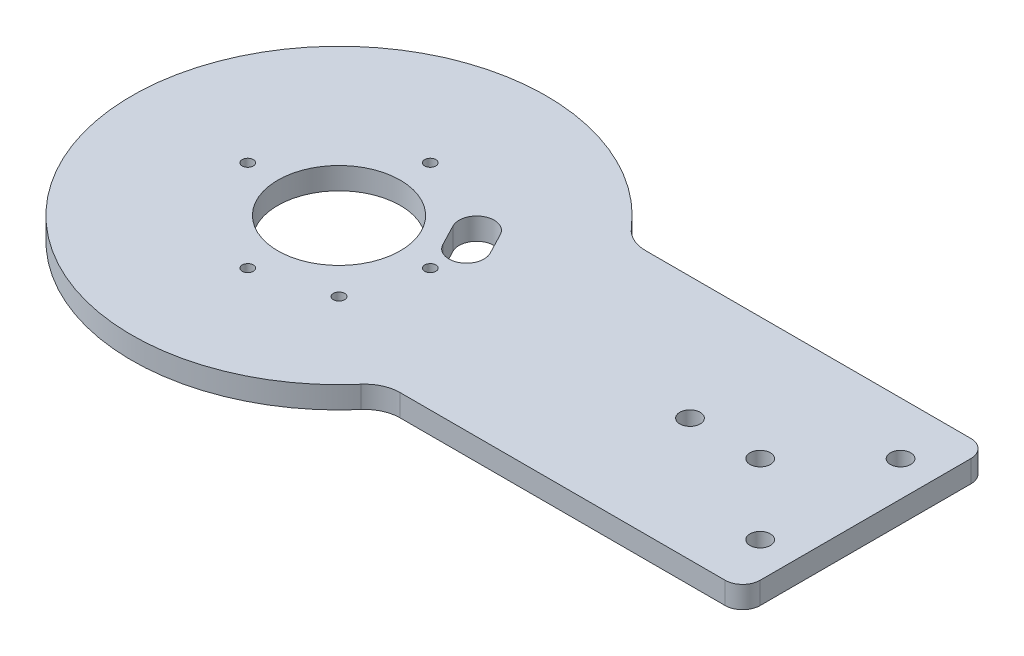
SolidWorks part; units mm, degrees
material "Acrylic (Medium-high impact)"
ref_plane "Front" through (0, 0, 0) normal (0, 0, 1) x (1, 0, 0)
ref_plane "Top" through (0, 0, 0) normal (0, 1, 0) x (1, 0, 0)
ref_plane "Right" through (0, 0, 0) normal (1, 0, 0) x (0, 0, -1)
sketch "Sketch1" plane through (0, 0, 0) normal (0, 1, 0) x (1, 0, 0)
  line L0 (177.8, 0) -> (0, 0) construction
  line L1 (190.5, -44.45) -> (60.41, -44.45)
  line L2 (190.5, 44.45) -> (60.41, 44.45)
  line L3 (190.5, 44.45) -> (190.5, -44.45)
  circle A2 centre (0, 0) radius 21.9583 construction
  arc A4 (60.41, 44.45) -> (60.41, -44.45) centre (0, 0) ccw
  point P3 (0, 0)
  dimension "D1" = 177.8
  dimension "D3" = 43.9166
  dimension "D4" = 44.45
  dimension "D5" = 75.0011
  dimension "D2" = 88.9
  dimension "D6" = 12.7
extrude "Boss-Extrude1" add sketch "Sketch1" along normal blind 7.9375
sketch "Sketch23" plane through (0, 0, 0) normal (0, -1, 0) x (1, 0, 0)
  line L0 (29.5483, -20.2499) -> (33.5359, -12.5897) construction
  line L1 (23.9158, -17.3178) -> (27.9034, -9.6576)
  line L2 (35.1808, -23.182) -> (39.1685, -15.5218)
  line L3 (0, 0) -> (-86.9571, 0) construction
  line L4 (29.5483, -20.2499) -> (0, 0) construction
  line L5 (0, 0) -> (33.5359, -12.5897) construction
  line L6 (0, 0) -> (31.5421, -16.4198) construction
  circle A0 centre (0, 0) radius 22.1615
  circle A1 centre (0, 0) radius 33.02 construction
  circle A2 centre (0, 33.02) radius 2.0193
  circle A3 centre (33.02, 0) radius 2.0193
  circle A4 centre (0, -33.02) radius 2.0193
  circle A5 centre (-33.02, 0) radius 2.0193
  circle A6 centre (25.4, 25.4) radius 2.0193
  arc A7 (23.9158, -17.3178) -> (35.1808, -23.182) centre (29.5483, -20.2499) ccw
  arc A8 (39.1685, -15.5218) -> (27.9034, -9.6576) centre (33.5359, -12.5897) ccw
  point P16 (31.5421, -16.4198)
  dimension "D1" = 44.323
  dimension "D3" = 4.0386
  dimension "D7" = 6.35
  dimension "D2" = 33.02
  dimension "D4" = 25.4
  dimension "D5" = 25.4
  dimension "D6" = 27.5
  dimension "D8" = 8.636
  dimension "D9" = 35.56
extrude "Cut-Extrude4" cut sketch "Sketch23" against normal through all
hole_wizard "L (0.29) Diameter Hole1" positions "Sketch21" profile "Sketch22" hole size "L" standard "ANSI Inch" end condition through all
sketch "Sketch21" plane through (0, 7.9375, 0) normal (0, 1, 0) x (1, 0, 0)
  line L0 (177.8, -25.4) -> (177.8, 25.4) construction
  line L3 (190.5, -44.45) -> (190.5, 44.45) construction
  point P0 (177.8, 25.4)
  point P2 (177.8, -25.4)
  point P11 (177.8, 0)
  point P20 (152.4, 0)
  point P27 (127, 0)
  dimension "D1" = 50.8
  dimension "D2" = 12.7
  dimension "D3" = 25.4
  dimension "D4" = 25.4
sketch "Sketch22" plane through (177.8, 7.9375, -25.4) normal (1, 0, 0) x (0, 0, 1)
  line L0 (0, 0) -> (0, 7.9375)
  line L1 (0, 7.9375) -> (3.683, 7.9375)
  line L2 (3.683, 7.9375) -> (3.683, 0)
  line L5 (3.683, 0) -> (0, 0)
  line L11 (0, -6.35) -> (0, 107.95) construction
  dimension "Thru Hole Dia." = 7.366
  dimension "Thru Hole Depth" = 7.9375
fillet "Fillet2" radius 6.35 2 edges at (190.5, 3.9688, 44.45) (190.5, 3.9688, -44.45)
fillet "Fillet3" radius 12.7 2 edges at (60.41, 3.9688, -44.45) (60.41, 3.9688, 44.45)
